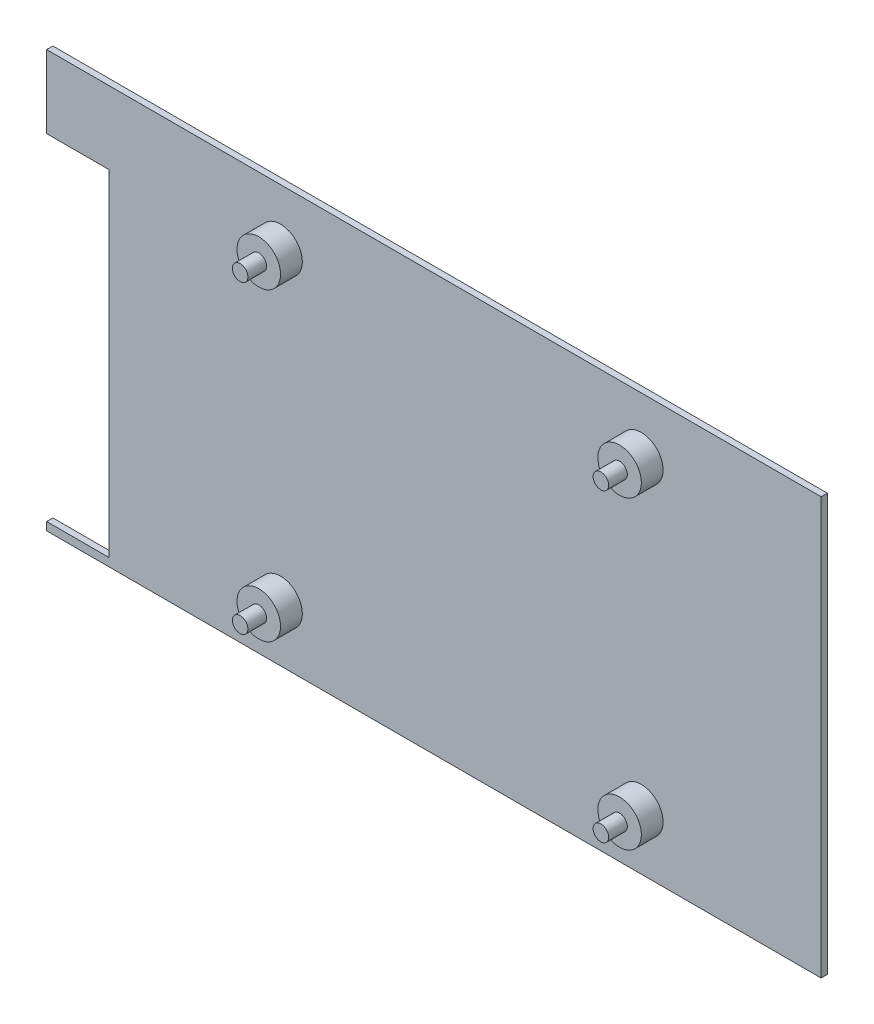
SolidWorks part; units mm, degrees
ref_plane "Front Plane" through (0, 0, 0) normal (0, 0, 1) x (1, 0, 0)
ref_plane "Top Plane" through (0, 0, 0) normal (0, 1, 0) x (1, 0, 0)
ref_plane "Right Plane" through (0, 0, 0) normal (1, 0, 0) x (0, 0, -1)
sketch "Sketch1" plane through (0, 0, 0) normal (0, 0, 1) x (1, 0, 0)
  line L0 (-61.85, 33.5) -> (-61.85, 21.8)
  line L1 (62.65, 33.5) -> (-61.85, 33.5)
  line L2 (62.65, 33.5) -> (62.65, -33.5)
  line L3 (62.65, -33.5) -> (-61.85, -33.5)
  line L4 (-61.85, 21.8) -> (-51.85, 21.8)
  line L5 (62.65, 33.5) -> (-61.85, -33.5) construction
  line L6 (62.65, -33.5) -> (-61.85, 33.5) construction
  line L7 (-51.85, 21.8) -> (-51.85, -32.2)
  line L8 (-51.85, -32.2) -> (-61.85, -32.2)
  line L9 (-61.85, -32.2) -> (-61.85, -33.5)
  point P0 (0.4, 0)
  dimension "D1" = 67
  dimension "D2" = 124.5
extrude "Boss-Extrude1" add sketch "Sketch1" along normal blind 1
sketch "Sketch2" plane through (0, 0, 1) normal (0, 0, 1) x (1, 0, 0)
  line L0 (4.75, 0) -> (0, 0) construction
  line L1 (33.75, 24.5) -> (-24.25, 24.5) construction
  line L2 (33.75, 24.5) -> (33.75, -24.5) construction
  line L3 (33.75, -24.5) -> (-24.25, -24.5) construction
  line L4 (-24.25, 24.5) -> (-24.25, -24.5) construction
  line L5 (33.75, 24.5) -> (-24.25, -24.5) construction
  line L6 (33.75, -24.5) -> (-24.25, 24.5) construction
  line L8 (-61.85, 33.5) -> (-23.85, 33.5) construction
  line L9 (62.65, 33.5) -> (-61.85, 33.5) construction
  circle A0 centre (-24.25, 24.5) radius 3.5
  circle A1 centre (33.75, 24.5) radius 3.5
  circle A2 centre (33.75, -24.5) radius 3.5
  circle A3 centre (-24.25, -24.5) radius 3.5
  point P0 (4.75, 0)
  dimension "D4" = 7
  dimension "D1" = 58
  dimension "D2" = 49
  dimension "D3" = 38
extrude "Boss-Extrude2" add sketch "Sketch2" along normal blind 3.5
sketch "Sketch3" plane through (0, 0, 4.5) normal (0, 0, 1) x (1, 0, 0)
  circle A0 centre (-24.25, 24.5) radius 1.25
  circle A1 centre (33.75, 24.5) radius 1.25
  circle A2 centre (33.75, -24.5) radius 1.25
  circle A3 centre (-24.25, -24.5) radius 1.25
  dimension "D1" = 2.5
extrude "Boss-Extrude3" add sketch "Sketch3" along normal blind 3
